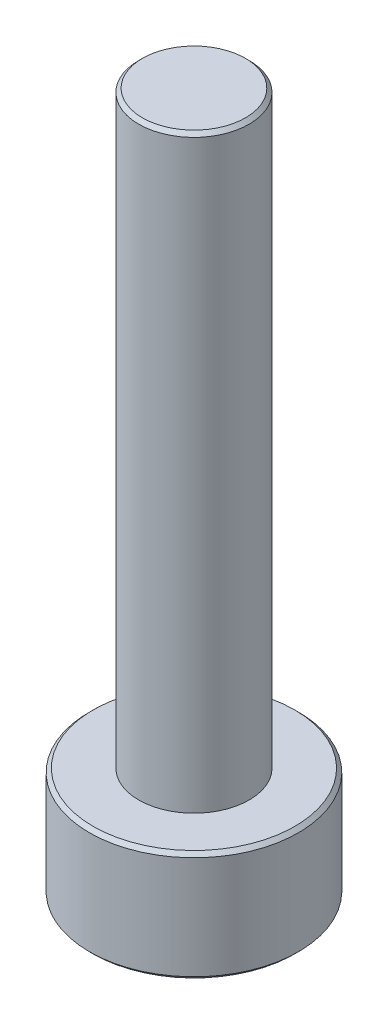
SolidWorks part; units mm, degrees
material "Q235"
ref_plane "前视基准面" through (0, 0, 0) normal (0, 0, 1) x (1, 0, 0)
ref_plane "上视基准面" through (0, 0, 0) normal (0, 1, 0) x (1, 0, 0)
ref_plane "右视基准面" through (0, 0, 0) normal (1, 0, 0) x (0, 0, -1)
sketch "草图1" plane through (0, 0, 0) normal (0, 1, 0) x (1, 0, 0)
  circle A0 centre (0, 0) radius 2.84
  dimension "D1" = 5.68
extrude "杯头部分" add sketch "草图1" along normal blind 3
sketch "草图2" plane through (0, 3, 0) normal (0, 1, 0) x (1, 0, 0)
  circle A0 centre (0, 0) radius 1.5
  dimension "D1" = 3
extrude "螺柱部分" add sketch "草图2" along normal blind 16
cosmetic thread "装饰螺纹线1" parameters "D2"=2.459
sketch "草图3" plane through (0, 0, 0) normal (0, -1, 0) x (1, 0, 0)
  line L1 (1.29, -0.7448) -> (1.29, 0.7448)
  line L2 (1.29, 0.7448) -> (0, 1.4896)
  line L3 (0, 1.4896) -> (-1.29, 0.7448)
  line L4 (-1.29, 0.7448) -> (-1.29, -0.7448)
  line L5 (-1.29, -0.7448) -> (0, -1.4896)
  line L6 (0, -1.4896) -> (1.29, -0.7448)
  circle A0 centre (0, 0) radius 1.29 construction
  dimension "D1" = 2.58
extrude "沉头内六角" cut sketch "草图3" against normal blind 1.3
chamfer "修饰性倒角" distance 0.1 angle 45 3 edges at (0, 19, 1.5) (0, 3, 2.84) (0, 0, 2.84)
